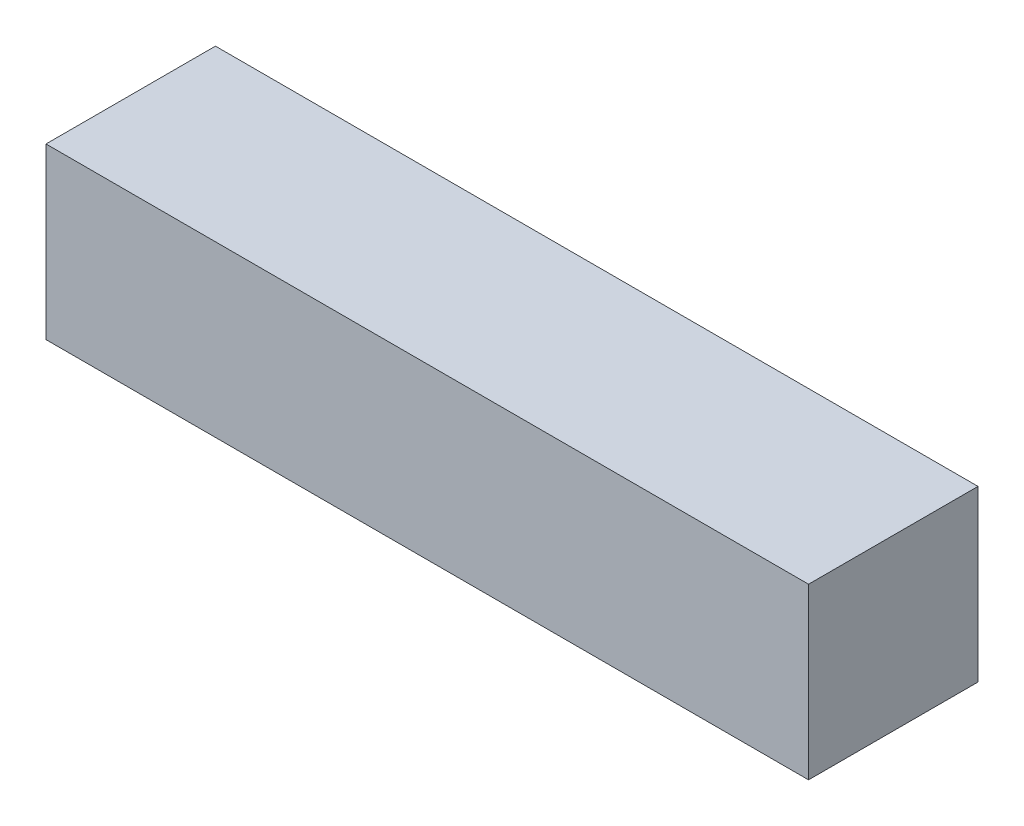
SolidWorks part; units mm, degrees
ref_plane "Plan de face" through (0, 0, 0) normal (0, 0, 1) x (1, 0, 0)
ref_plane "Plan de dessus" through (0, 0, 0) normal (0, 1, 0) x (1, 0, 0)
ref_plane "Plan de droite" through (0, 0, 0) normal (1, 0, 0) x (0, 0, -1)
sketch "Esquisse1" plane through (0, 0, 0) normal (0, 0, 1) x (1, 0, 0)
  line L1 (0, 0) -> (270, 0)
  line L2 (0, 0) -> (0, 60)
  line L3 (0, 60) -> (270, 60)
  line L4 (270, 0) -> (270, 60)
  dimension "D1" = 270
  dimension "D2" = 60
extrude "Boss.-Extru.1" add sketch "Esquisse1" along normal blind 60
